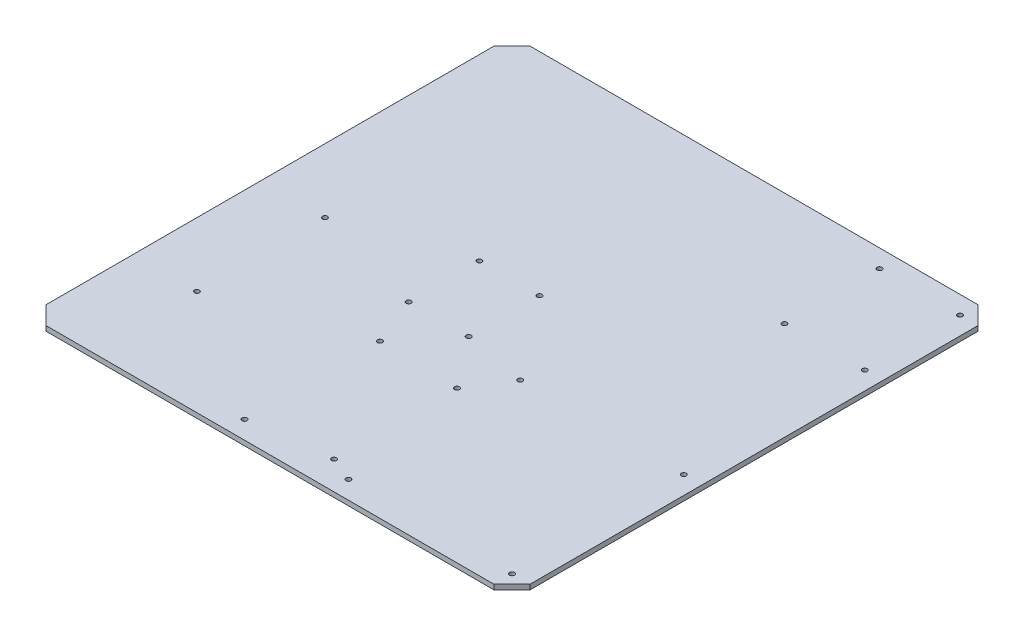
SolidWorks part; units mm, degrees
ref_plane "Front Plane" through (0, 0, 0) normal (0, 0, 1) x (1, 0, 0)
ref_plane "Top Plane" through (0, 0, 0) normal (0, 1, 0) x (1, 0, 0)
ref_plane "Right Plane" through (0, 0, 0) normal (1, 0, 0) x (0, 0, -1)
sketch "Sketch1" plane through (0, 0, 0) normal (0, 1, 0) x (1, 0, 0)
  line L0 (-147.5, 136.5) -> (-136.5, 147.5)
  line L1 (-136.5, -147.5) -> (136.5, -147.5)
  line L2 (-147.5, -136.5) -> (-147.5, 136.5)
  line L3 (-136.5, 147.5) -> (136.5, 147.5)
  line L4 (147.5, -136.5) -> (147.5, 136.5)
  line L5 (-147.5, -147.5) -> (147.5, 147.5) construction
  line L6 (-147.5, 147.5) -> (147.5, -147.5) construction
  line L7 (-147.5, 147.5) -> (-147.5, 136.5) construction
  line L8 (-136.5, 147.5) -> (-147.5, 147.5) construction
  line L9 (136.5, 147.5) -> (147.5, 136.5)
  line L10 (147.5, -136.5) -> (136.5, -147.5)
  line L11 (-147.5, -136.5) -> (-136.5, -147.5)
  line L12 (-147.5, -136.5) -> (-147.5, -147.5) construction
  line L13 (-147.5, -147.5) -> (-136.5, -147.5) construction
  line L14 (136.5, -147.5) -> (147.5, -147.5) construction
  line L15 (147.5, -147.5) -> (147.5, -136.5) construction
  line L16 (147.5, 136.5) -> (147.5, 147.5) construction
  line L17 (147.5, 147.5) -> (136.5, 147.5) construction
  circle A0 centre (-26.5, -136.5) radius 1.5
  circle A1 centre (-26.5, -54) radius 1.5
  circle A2 centre (21.8, -55.3) radius 1.5
  circle A3 centre (21.8, -130.2) radius 1.5
  circle A4 centre (-108.5, -83.5) radius 1.5
  circle A5 centre (-108.5, -5.5) radius 1.5
  circle A7 centre (-38.5, -24.5) radius 1.5
  circle A8 centre (-1.92, 18.68) radius 1.5
  circle A9 centre (-38.5, 18.68) radius 1.5
  circle A10 centre (-1.92, -24.5) radius 1.5
  circle A11 centre (136.5, 136.5) radius 1.5
  circle A12 centre (87.5, 136.5) radius 1.5
  circle A13 centre (87.5, 78.5) radius 1.5
  circle A14 centre (136.5, 78.5) radius 1.5
  circle A15 centre (136.5, -136.5) radius 1.5
  circle A16 centre (36.8, -136.5) radius 1.5
  circle A17 centre (36.8, -31.8) radius 1.5
  circle A18 centre (136.5, -31.8) radius 1.5
  point P0 (0, 0)
  point P45 (-142, 142)
  dimension "D2" = 3
  dimension "D3" = 121
  dimension "D4" = 11
  dimension "D5" = 6.3
  dimension "D6" = 48.3
  dimension "D7" = 81.2
  dimension "D8" = 82.5
  dimension "D9" = 3
  dimension "D10" = 39
  dimension "D11" = 64
  dimension "D12" = 78
  dimension "D13" = 109
  dimension "D14" = 123
  dimension "D15" = 3
  dimension "D16" = 36.58
  dimension "D17" = 43.18
  dimension "D18" = 3
  dimension "D19" = 11
  dimension "D20" = 11
  dimension "D21" = 49
  dimension "D22" = 58
  dimension "D23" = 3
  dimension "D24" = 11
  dimension "D26" = 99.7
  dimension "D25" = 11
  dimension "D27" = 104.7
  dimension "D28" = 295
  dimension "D29" = 11
extrude "Boss-Extrude1" add sketch "Sketch1" along normal mid plane 3
